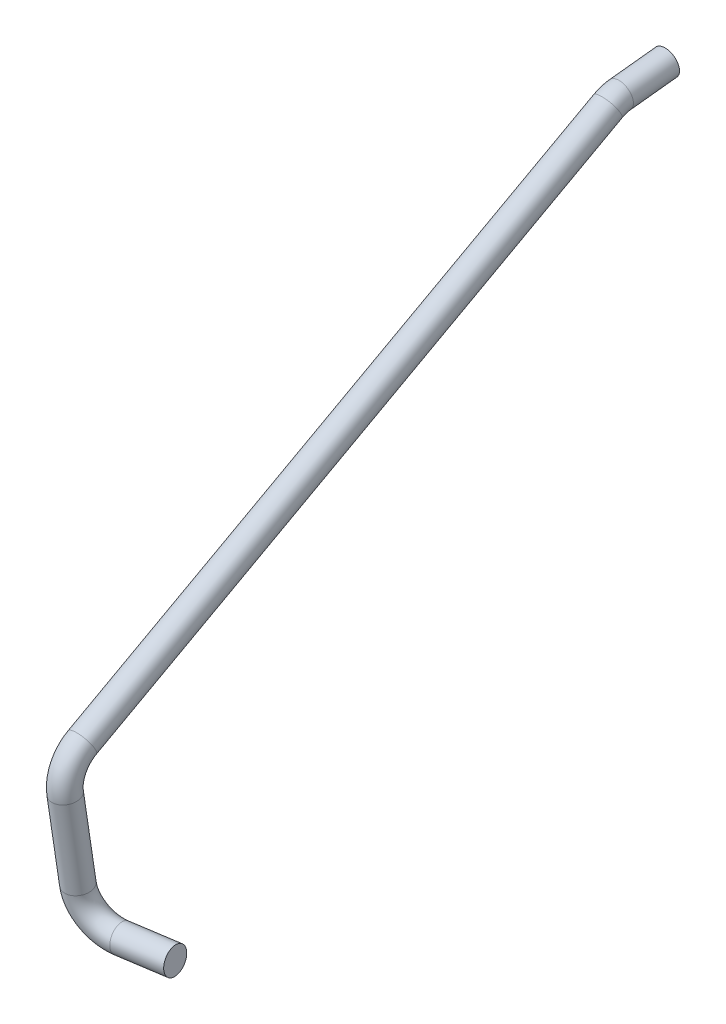
SolidWorks part; units mm, degrees
ref_plane "Front Plane" through (0, 0, 0) normal (0, 0, 1) x (1, 0, 0)
ref_plane "Top Plane" through (0, 0, 0) normal (0, 1, 0) x (1, 0, 0)
ref_plane "Right Plane" through (0, 0, 0) normal (1, 0, 0) x (0, 0, -1)
sketch3d "3DSketch1"
  line L3 (-14.7, 0.02, -8) -> (-14.7, -2.9018, 18.6186)
  line L4 (-14.6734, -5.156, 25.8874) -> (-12.2955, -169.0602, 331.6131)
  line L5 (-11.8528, -189.2241, 342.0006) -> (-10.6332, -237.0454, 335.8706)
  line L6 (9.7469, -256.0942, 331.1775) -> (37.8048, -254.9813, 328.1416)
  circle A4 centre (-14.7, 0.02, -8) radius 9.2 construction
  circle A5 centre (37.8048, -254.9813, 328.1416) radius 4.5 construction
  arc A6 (-14.7, -2.9018, 18.6186) -> (-14.6734, -5.156, 25.8874) centre (-14.333, -22.779, 16.4368) ccw
  arc A7 (-12.2955, -169.0602, 331.6131) -> (-11.8528, -189.2241, 342.0006) centre (-11.8065, -186.68, 322.1631) ccw
  arc A8 (-10.6332, -237.0454, 335.8706) -> (9.7469, -256.0942, 331.1775) centre (9.2354, -236.263, 333.7202) ccw
  point P6 (-14.7, 0.02, 1.2)
  point P11 (33.3048, -254.9754, 328.1296)
  point P12 (60.6393, -230.6608, 302.5471)
  point P13 (52.8249, -251.9602, 322.0407)
  point P14 (-10.1274, -256.8824, 333.3279)
  point P15 (60.6393, -230.6608, 302.5471)
  point P16 (60.6393, -230.6608, 302.5471)
  point P18 (60.6393, -230.6608, 302.5471)
  point P19 (0, 0, 0)
  point P20 (-12.2011, -175.5676, 343.7511)
  point P21 (38.7359, -264.3522, 321.2443)
  point P22 (35.1131, -267.5385, 321.0396)
  point P23 (14.8784, -229.4432, 208.1657)
  point P26 (-14.7, -3.3247, 22.4715)
  point P27 (5.6636, -22.4142, 16.4769)
  point P30 (-12.2011, -175.5676, 343.7511)
  point P31 (8.1871, -186.1843, 322.2733)
  point P34 (-10.1274, -256.8824, 333.3279)
  point P35 (11.4672, -238.734, 353.441)
  dimension "D1" = 20
sweep "Sweep1" add path "3DSketch1" circular profile diameter 15 parameters "D3"=15
